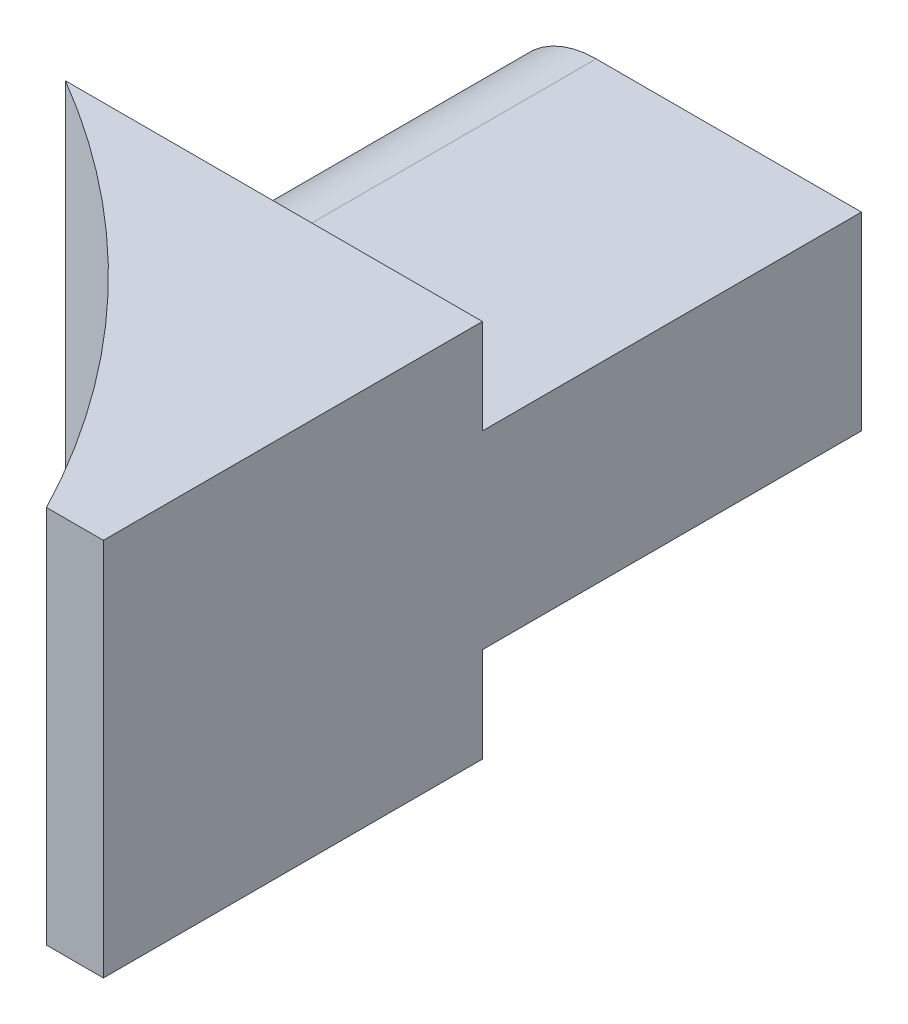
SolidWorks part; units mm, degrees
ref_plane "Alzado" through (0, 0, 0) normal (0, 0, 1) x (1, 0, 0)
ref_plane "Planta" through (0, 0, 0) normal (0, 1, 0) x (1, 0, 0)
ref_plane "Vista lateral" through (0, 0, 0) normal (1, 0, 0) x (0, 0, -1)
sketch "Croquis1" plane through (0, 0, 0) normal (0, 0, 1) x (1, 0, 0)
  circle A0 centre (0, 0) radius 2.5
  dimension "D1" = 5
extrude "Saliente-Extruir1" add sketch "Croquis1" along normal blind 10
sketch "Croquis2" plane through (0, 0, 0) normal (0, 0, -1) x (-1, 0, 0)
  circle A0 centre (0, 0) radius 1.5
  dimension "D1" = 3
extrude "Cortar-Extruir1" cut sketch "Croquis2" against normal blind 0.9
fillet "Redondeo1" radius 0.1 1 edges at (-1.5, 0, 0.9)
sketch "Croquis3" plane through (0, 0, 10) normal (0, 0, 1) x (1, 0, 0)
  line L0 (0, 2.5) -> (0, -2.5) construction
  line L1 (-4, 5) -> (7, 5)
  line L2 (-4, 5) -> (-4, -5)
  line L3 (-4, -5) -> (7, -5)
  line L4 (7, 5) -> (7, -5)
  line L5 (-2.5, 0) -> (2.5, 0) construction
  circle A0 centre (0, 0) radius 2.5 construction
  dimension "D1" = 4
  dimension "D2" = 7
  dimension "D3" = 5
  dimension "D4" = 5
extrude "Saliente-Extruir2" add sketch "Croquis3" along normal blind 10
sketch "Croquis4" plane through (0, -5, 0) normal (0, -1, 0) x (1, 0, 0)
  line L0 (-4, 10) -> (-4, 12) construction
  line L1 (-4, 20) -> (-4, 10) construction
  line L4 (-4, 20) -> (-4, 10)
  line L5 (-4, 20) -> (5.5, 20)
  line L6 (-4, 20) -> (7, 20) construction
  arc A2 (5.5, 20) -> (-4, 10) centre (-16.6717, 31.5506) cw
  dimension "D1" = 9.5
  dimension "D2" = 25
extrude "Cortar-Extruir2" cut sketch "Croquis4" against normal through all
sketch "Croquis5" plane through (0, 0, 0) normal (0, 0, -1) x (-1, 0, 0)
  line L0 (0, -2.5) -> (-7, -2.5)
  line L1 (-7, -2.5) -> (-7, 2.5)
  line L2 (-7, 2.5) -> (0, 2.5)
  circle A0 centre (0, 0) radius 2.5 construction
  arc A1 (0, -2.5) -> (0, 2.5) centre (0, 0) cw
  dimension "D1" = 7
  dimension "D2" = 7
  dimension "D3" = 5
extrude "Saliente-Extruir3" add sketch "Croquis5" against normal blind 10
